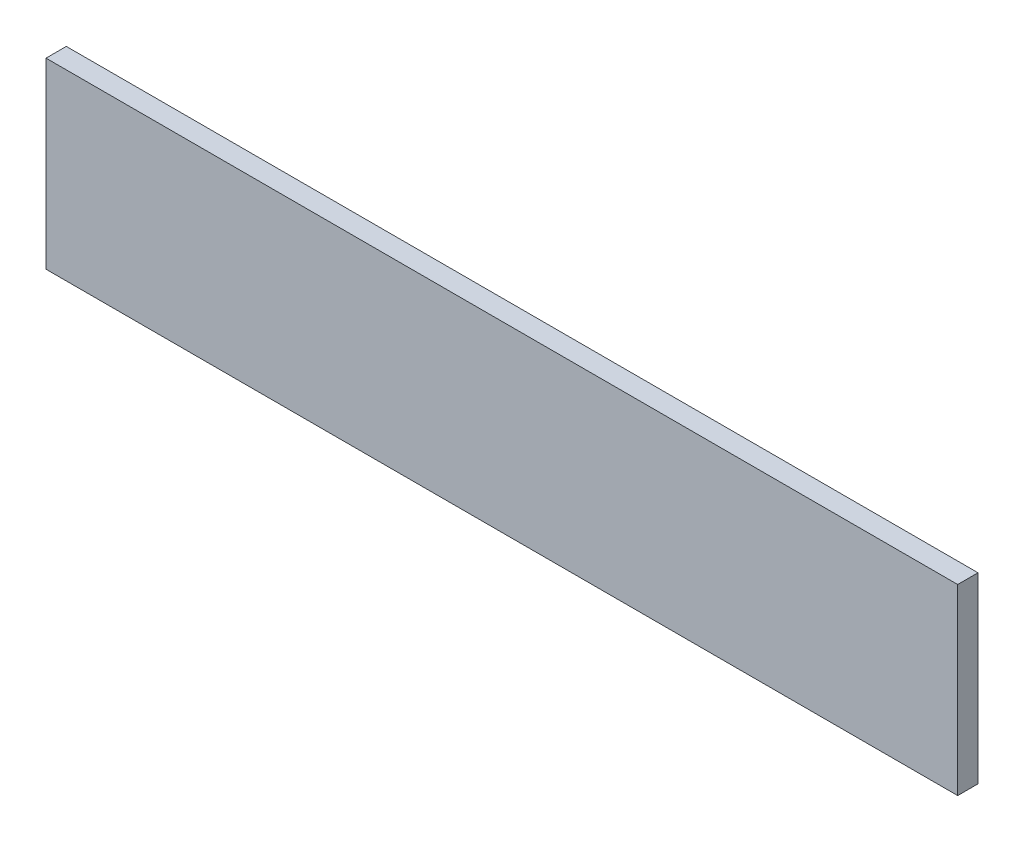
SolidWorks part; units mm, degrees
ref_plane "Front Plane" through (0, 0, 0) normal (0, 0, 1) x (1, 0, 0)
ref_plane "Top Plane" through (0, 0, 0) normal (0, 1, 0) x (1, 0, 0)
ref_plane "Right Plane" through (0, 0, 0) normal (1, 0, 0) x (0, 0, -1)
sketch "Sketch1" plane through (0, 0, 0) normal (0, 0, 1) x (1, 0, 0)
  line L1 (0, 0) -> (1139.952, 0)
  line L2 (0, 0) -> (0, 228.6)
  line L3 (0, 228.6) -> (1139.952, 228.6)
  line L4 (1139.952, 0) -> (1139.952, 228.6)
  dimension "D1" = 1139.952
  dimension "D2" = 228.6
extrude "Boss-Extrude1" add sketch "Sketch1" along normal mid plane 25.4
